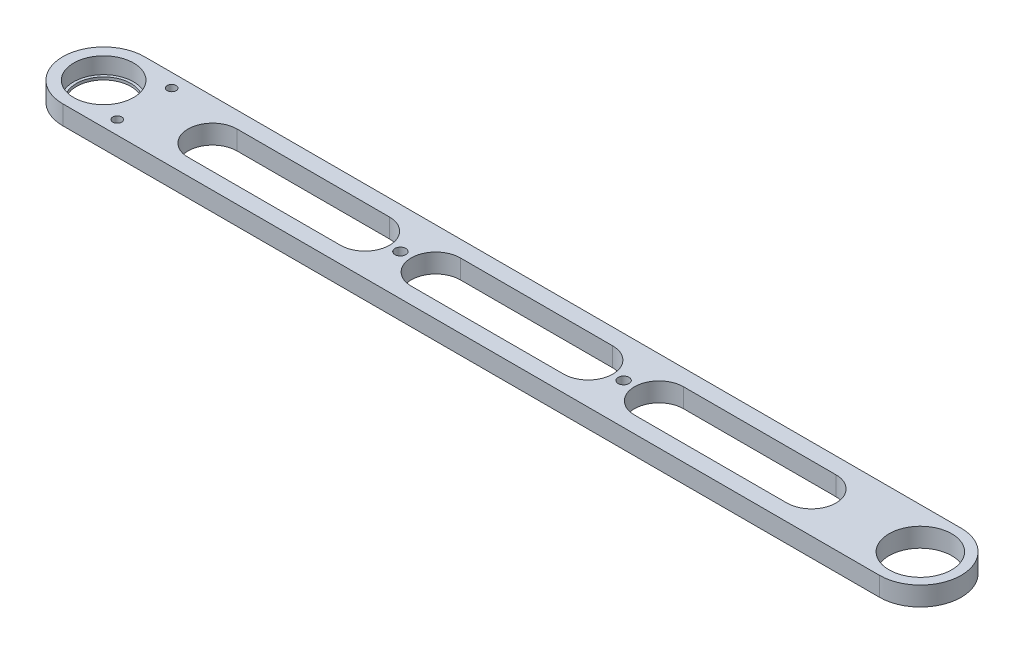
SolidWorks part; units mm, degrees
material "1060 Alloy"
ref_plane "Front Plane" through (0, 0, 0) normal (0, 0, 1) x (1, 0, 0)
ref_plane "Top Plane" through (0, 0, 0) normal (0, 1, 0) x (1, 0, 0)
ref_plane "Right Plane" through (0, 0, 0) normal (1, 0, 0) x (0, 0, -1)
sketch "Sketch1" plane through (0, 0, 0) normal (0, 1, 0) x (1, 0, 0)
  line L0 (-44.2539, 0) -> (44.2539, 0) construction
  line L1 (0, 21.7575) -> (0, -21.3381) construction
  line L2 (0, -44.7868) -> (0, 44.7868) construction
  line L3 (150, -15) -> (-150, -15)
  line L4 (-150, 15) -> (150, 15)
  line L5 (110, 9) -> (54, 9)
  line L6 (28, 9) -> (-28, 9)
  line L7 (-54, 9) -> (-110, 9)
  line L8 (-110, -9) -> (-54, -9)
  line L9 (-28, -9) -> (28, -9)
  line L10 (54, -9) -> (110, -9)
  line L11 (-45, 0) -> (-37, 0) construction
  line L12 (45, 0) -> (37, 0) construction
  arc A0 (-150, 15) -> (-150, -15) centre (-150, 0) ccw
  arc A1 (150, -15) -> (150, 15) centre (150, 0) ccw
  circle A2 centre (150, 0) radius 11.5
  circle A3 centre (-150, 0) radius 10
  arc A4 (-110, -9) -> (-110, 9) centre (-110, 0) cw
  arc A5 (-54, -9) -> (-54, 9) centre (-54, 0) ccw
  arc A6 (-28, -9) -> (-28, 9) centre (-28, 0) cw
  arc A7 (28, -9) -> (28, 9) centre (28, 0) ccw
  arc A8 (54, -9) -> (54, 9) centre (54, 0) cw
  arc A9 (110, -9) -> (110, 9) centre (110, 0) ccw
  circle A10 centre (41, 0) radius 2
  circle A11 centre (-41, 0) radius 2
  dimension "D2" = 15
  dimension "D3" = 6
  dimension "D6" = 26
  dimension "D8" = 4
  dimension "D1" = 150
  dimension "D4" = 40
  dimension "D5" = 26
  dimension "D7" = 40
extrude "Boss-Extrude1" add sketch "Sketch1" along normal blind 7
sketch "Sketch2" plane through (0, 7, 0) normal (0, 1, 0) x (1, 0, 0)
  circle A0 centre (-150, 0) radius 11
extrude "Cut-Extrude1" cut sketch "Sketch2" against normal blind 6
hole_wizard "M4 Tapped Hole1" positions "Sketch3" profile "Sketch4" tap size "M4" standard "ISO"
sketch "Sketch3" plane through (0, 7, 0) normal (0, 1, 0) x (1, 0, 0)
  line L0 (-150, -15) -> (150, -15) construction
  line L1 (-150, 0) -> (-109.2137, 0) construction
  point P0 (-135, 10)
  point P2 (-135, -10)
  dimension "D1" = 5
  dimension "D2" = 15
sketch "Sketch4" plane through (-135, 7, -10) normal (1, 0, 0) x (0, 0, 1)
  line L0 (0, 0) -> (0, 5.9914)
  line L1 (0, 5.9914) -> (1.65, 5)
  line L2 (1.65, 5) -> (1.65, 0)
  line L5 (1.65, 0) -> (0, 0)
  line L10 (0, 5.9914) -> (-1.65, 5) construction
  line L11 (0, -6.35) -> (0, 107.95) construction
  dimension "Tap Drill Dia." = 3.3
  dimension "Tap Drill Depth" = 5
  dimension "Drill Angle" = 118
cosmetic thread "Hole Thread1" parameters "D1"=5, "D2"=4
cosmetic thread "Hole Thread2" parameters "D1"=5, "D2"=4
